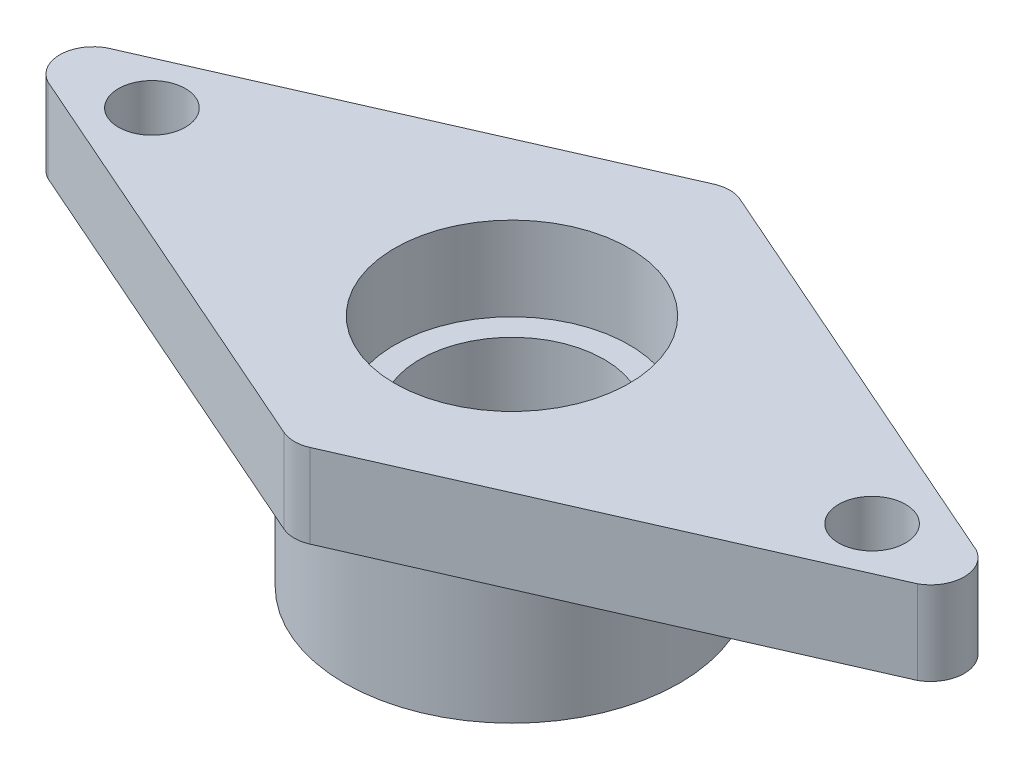
SolidWorks part; units mm, degrees
ref_plane "Front Plane" through (0, 0, 0) normal (0, 0, 1) x (1, 0, 0)
ref_plane "Top Plane" through (0, 0, 0) normal (0, 1, 0) x (1, 0, 0)
ref_plane "Right Plane" through (0, 0, 0) normal (1, 0, 0) x (0, 0, -1)
sketch "Sketch2" plane through (0, 0, 0) normal (0, 0, 1) x (1, 0, 0)
  line L0 (0, 0) -> (0, 14.9615) construction
  line L1 (5.5, 0) -> (10, 0)
  line L2 (10, 0) -> (10, -9)
  line L3 (5.5, 0) -> (5.5, -6.5)
  line L4 (10, -9) -> (5.5, -6.5)
  dimension "D1" = 4.5
  dimension "D2" = 10
  dimension "D3" = 9
  dimension "D4" = 6.5
revolve "Revolve1" add sketch "Sketch2" angle 360 about L0
sketch "Sketch3" plane through (0, 0, 0) normal (0, 1, 0) x (1, 0, 0)
  line L0 (0, 0) -> (0, 13) construction
  line L1 (27, 0) -> (-27, 0) construction
  line L2 (-0.7809, 12.8358) -> (-25.9569, 1.7562)
  line L3 (0.7809, 12.8358) -> (25.9569, 1.7562)
  line L4 (-0.7809, -12.8358) -> (-25.9569, -1.7562)
  line L5 (0.7809, -12.8358) -> (25.9569, -1.7562)
  circle A0 centre (0, 0) radius 7
  circle A1 centre (21.5, 0) radius 2
  circle A2 centre (-21.5, 0) radius 2
  arc A3 (-25.9569, -1.7562) -> (-25.9569, 1.7562) centre (-25, 0) cw
  arc A4 (0, 13) -> (-0.7809, 12.8358) centre (0, 11.0613) ccw
  arc A5 (0, 13) -> (0.7809, 12.8358) centre (0, 11.0613) cw
  arc A6 (25.9569, -1.7562) -> (25.9569, 1.7562) centre (25, 0) ccw
  arc A7 (0, -13) -> (0.7809, -12.8358) centre (0, -11.0613) ccw
  arc A8 (0, -13) -> (-0.7809, -12.8358) centre (0, -11.0613) cw
  dimension "D2" = 4
  dimension "D4" = 4
  dimension "D1" = 21.5
  dimension "D3" = 21.5
  dimension "D5" = 13
  dimension "D6" = 54
extrude "Boss-Extrude1" add sketch "Sketch3" along normal blind 5
